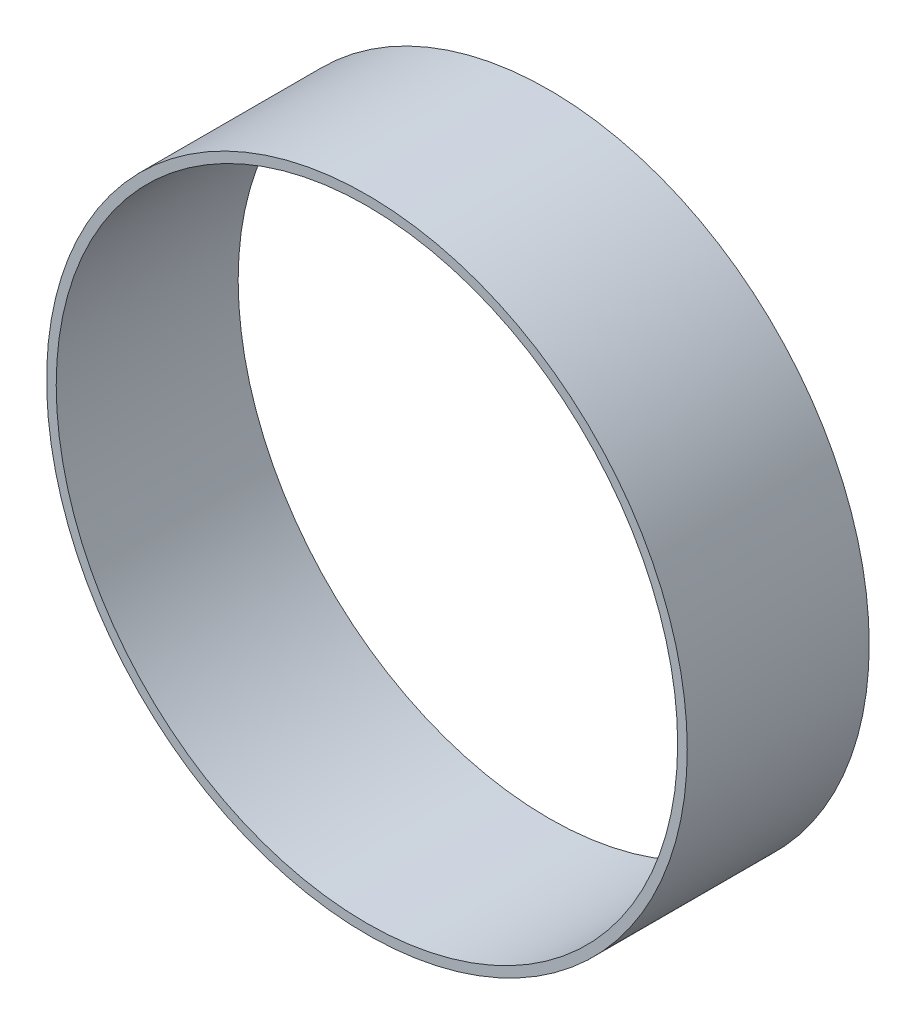
SolidWorks part; units mm, degrees
material "6061 Alloy"
ref_plane "Front Plane" through (0, 0, 0) normal (0, 0, 1) x (1, 0, 0)
ref_plane "Top Plane" through (0, 0, 0) normal (0, 1, 0) x (1, 0, 0)
ref_plane "Right Plane" through (0, 0, 0) normal (1, 0, 0) x (0, 0, -1)
sketch "Sketch1" plane through (0, 0, 0) normal (0, 0, 1) x (1, 0, 0)
  circle A0 centre (0, 0) radius 48.5
  circle A1 centre (0, 0) radius 50
  dimension "D1" = 97
  dimension "D2" = 100
extrude "Boss-Extrude1" add sketch "Sketch1" along normal blind 28.4
